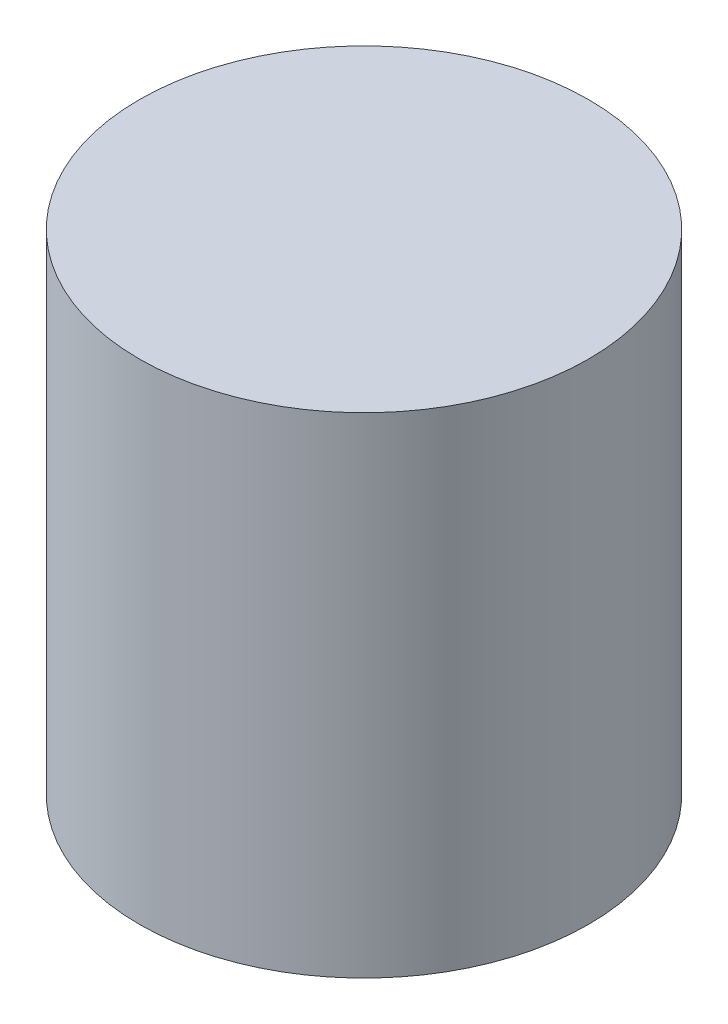
SolidWorks part; units mm, degrees
ref_plane "Front Plane" through (0, 0, 0) normal (0, 0, 1) x (1, 0, 0)
ref_plane "Top Plane" through (0, 0, 0) normal (0, 1, 0) x (1, 0, 0)
ref_plane "Right Plane" through (0, 0, 0) normal (1, 0, 0) x (0, 0, -1)
sketch "Sketch1" plane through (0, 0, 0) normal (0, 1, 0) x (1, 0, 0)
  circle A0 centre (0, 0) radius 15.6002
extrude "Boss-Extrude1" add sketch "Sketch1" along normal blind 34
